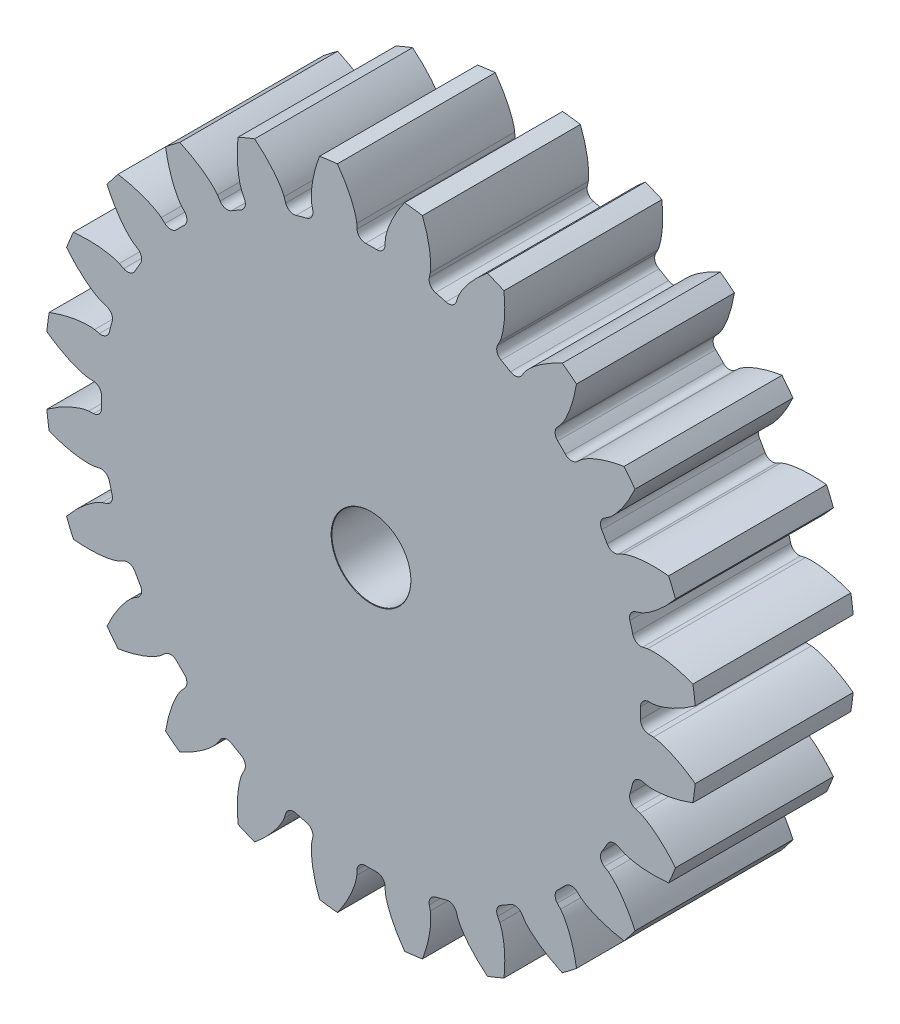
SolidWorks part; units mm, degrees
ref_plane "Front Plane" through (0, 0, 0) normal (0, 0, 1) x (1, 0, 0)
ref_plane "Top Plane" through (0, 0, 0) normal (0, 1, 0) x (1, 0, 0)
ref_plane "Right Plane" through (0, 0, 0) normal (1, 0, 0) x (0, 0, -1)
sketch "Sketch1" plane through (0, 0, 0) normal (0, 0, 1) x (1, 0, 0)
  line L0 (0, 0) -> (0, 19.05) construction
  line L1 (-6.1226, 21.2784) -> (6.1226, 16.8216) construction
  circle A0 centre (0, 0) radius 17.0656 construction
  circle A1 centre (0, 0) radius 20.6375 construction
  circle A2 centre (0, 0) radius 19.05 construction
  circle A3 centre (0, 0) radius 17.9011 construction
  point P8 (203.2, 0)
  point P13 (304.8, 0)
  dimension "OD | Outside Diameter" = 41.275
  dimension "Root Diameter" = 34.1313
  dimension "Gear Pitch Diameter" = 38.1
  dimension "Base Diameter" = 35.8023
  dimension "Pressure Angle" = 20
  dimension "Number of Teeth" = 609.6
  dimension "Gear Pitch | Diametral Pitch" = 406.4
sketch "Sketch2" plane through (0, 0, 0) normal (1, 0, 0) x (0, 0, -1)
  line L0 (-5, 0) -> (5, 0) construction
  point P2 (15.6375, 0)
  point P5 (25.9562, 0)
  point P6 (-15.6375, 0)
  dimension "Length" = 10
  dimension "D1" = 20.6375
  dimension "D2" = 30.9562
  dimension "D3" = 20.6375
sketch "Sketch3" plane through (0, 0, 0) normal (0, 0, 1) x (1, 0, 0)
  circle A0 centre (0, 0) radius 20.6375
  circle A1 centre (0, 0) radius 20.6375 construction
extrude "Boss-Extrude1" add sketch "Sketch3" against normal up to vertex (5 mm away) and the other way up to vertex (5 mm away) up to point (0, 0, -5) other way up to point (0, 0, 5)
sketch "Sketch4" plane through (0, 0, 0) normal (0, 0, 1) x (1, 0, 0)
  line L0 (0, 0) -> (17.0438, 0.8622) construction
  line L2 (0, 0) -> (17.0438, -0.8622) construction
  line L4 (17.0438, 0.8622) -> (17.8783, 0.9044)
  line L5 (17.8783, -0.9044) -> (17.0438, -0.8622)
  arc A0 (17.0438, 0.8622) -> (17.0438, -0.8622) centre (0, 0) cw
  arc A3 (20.5273, 2.1297) -> (20.5273, -2.1297) centre (0, 0) cw
  circle A4 centre (0, 0) radius 20.6375 construction
  spline S0 degree 4 poles (17.8783, 0.9044) (17.8826, 0.9047) (17.8948, 0.9056) (17.9178, 0.908) (17.9552, 0.9129) (18.0028, 0.9204) (18.0642, 0.9316) (18.1363, 0.9468) (18.2153, 0.9656) (18.3009, 0.9883) (18.3861, 1.013) (18.4708, 1.0393) (18.5549, 1.0673) (18.6565, 1.1031) (18.7778, 1.1487) (18.9188, 1.2059) (19.0779, 1.2755) (19.2391, 1.3513) (19.3967, 1.43) (19.555, 1.5141) (19.7073, 1.5988) (19.8644, 1.6914) (20.0088, 1.7793) (20.1693, 1.883) (20.2983, 1.9682) (20.4671, 2.0861) (20.5663, 2.1574) (20.6818, 2.2427) (20.7328, 2.2815) (20.7642, 2.3054) knots 0 0 0 0 0 0.005377 0.015084 0.028532 0.04661 0.064855 0.092111 0.119476 0.146842 0.174209 0.201575 0.228941 0.256307 0.307035 0.361767 0.4165 0.471232 0.525964 0.580697 0.635429 0.690161 0.744894 0.799626 0.854358 0.909091 0.954545 1 1 1 1 1 construction
  spline S1 degree 4 poles (17.8783, 0.9044) (17.8826, 0.9047) (17.8948, 0.9056) (17.9178, 0.908) (17.9552, 0.9129) (18.0028, 0.9204) (18.0642, 0.9316) (18.1363, 0.9468) (18.2153, 0.9656) (18.3009, 0.9883) (18.3861, 1.013) (18.4708, 1.0393) (18.5549, 1.0673) (18.6565, 1.1031) (18.7778, 1.1487) (18.9188, 1.2059) (19.0779, 1.2755) (19.2391, 1.3513) (19.3967, 1.43) (19.555, 1.5141) (19.7073, 1.5988) (19.8644, 1.6914) (20.0088, 1.7793) (20.1693, 1.883) (20.2983, 1.9682) (20.4305, 2.0606) (20.4946, 2.1061) (20.5273, 2.1297) knots 0 0 0 0 0 0.005377 0.015084 0.028532 0.04661 0.064855 0.092111 0.119476 0.146842 0.174209 0.201575 0.228941 0.256307 0.307035 0.361767 0.4165 0.471232 0.525964 0.580697 0.635429 0.690161 0.744894 0.799626 0.854358 0.909091 0.909091 0.909091 0.909091 0.909091
  spline S2 degree 4 poles (17.8783, -0.9044) (17.8826, -0.9047) (17.8948, -0.9056) (17.9178, -0.908) (17.9552, -0.9129) (18.0028, -0.9204) (18.0642, -0.9316) (18.1363, -0.9468) (18.2153, -0.9656) (18.3009, -0.9883) (18.3861, -1.013) (18.4708, -1.0393) (18.5549, -1.0673) (18.6565, -1.1031) (18.7778, -1.1487) (18.9188, -1.2059) (19.0779, -1.2755) (19.2391, -1.3513) (19.3967, -1.43) (19.555, -1.5141) (19.7073, -1.5988) (19.8644, -1.6914) (20.0088, -1.7793) (20.1693, -1.883) (20.2983, -1.9682) (20.4671, -2.0861) (20.5663, -2.1574) (20.6818, -2.2427) (20.7328, -2.2815) (20.7642, -2.3054) knots 0 0 0 0 0 0.005377 0.015084 0.028532 0.04661 0.064855 0.092111 0.119476 0.146842 0.174209 0.201575 0.228941 0.256307 0.307035 0.361767 0.4165 0.471232 0.525964 0.580697 0.635429 0.690161 0.744894 0.799626 0.854358 0.909091 0.954545 1 1 1 1 1 construction
  spline S3 degree 4 poles (17.8783, -0.9044) (17.8826, -0.9047) (17.8948, -0.9056) (17.9178, -0.908) (17.9552, -0.9129) (18.0028, -0.9204) (18.0642, -0.9316) (18.1363, -0.9468) (18.2153, -0.9656) (18.3009, -0.9883) (18.3861, -1.013) (18.4708, -1.0393) (18.5549, -1.0673) (18.6565, -1.1031) (18.7778, -1.1487) (18.9188, -1.2059) (19.0779, -1.2755) (19.2391, -1.3513) (19.3967, -1.43) (19.555, -1.5141) (19.7073, -1.5988) (19.8644, -1.6914) (20.0088, -1.7793) (20.1693, -1.883) (20.2983, -1.9682) (20.4305, -2.0606) (20.4946, -2.1061) (20.5273, -2.1297) knots 0 0 0 0 0 0.005377 0.015084 0.028532 0.04661 0.064855 0.092111 0.119476 0.146842 0.174209 0.201575 0.228941 0.256307 0.307035 0.361767 0.4165 0.471232 0.525964 0.580697 0.635429 0.690161 0.744894 0.799626 0.854358 0.909091 0.909091 0.909091 0.909091 0.909091
  dimension "D1" = 34.1313
extrude "Cut-Extrude1" cut sketch "Sketch4" against normal through all both and the other way through all
fillet "Fillet1" radius 0.5326 2 edges at (17.0438, -0.8622, 0) (17.0438, 0.8622, 0)
pattern_circular "CirPattern1" count 24 over 360 about axis through (0, 0, 5) along (0, 0, -1) of "Cut-Extrude1", "Fillet1"
sketch "Sketch5" plane through (0, 0, 5) normal (0, 0, 1) x (1, 0, 0)
  point P0 (0, 0)
hole_wizard "Ø5.0mm Dowel Hole1" positions "Sketch5" profile "Sketch6" hole size "Ø5.0" standard "ANSI Metric" end condition through all
sketch "Sketch6" plane through (0, 0, 5) normal (1, 0, 0) x (0, -1, 0)
  line L0 (0, 0) -> (0, 10)
  line L1 (0, 10) -> (2.5, 10)
  line L2 (2.5, 10) -> (2.5, 0.025)
  line L3 (2.5, 0.025) -> (2.525, 0)
  line L5 (2.525, 0) -> (0, 0)
  line L6 (-2.5, 0.025) -> (-2.525, 0) construction
  line L11 (0, -6.35) -> (0, 107.95) construction
  dimension "Thru Hole Dia." = 5
  dimension "Thru Hole Depth" = 10
  dimension "Near C'Sink Dia." = 5.05
  dimension "Near C'Sink Angle" = 90
equation "\"Root Diameter@Sketch1\"=\"Root Diameter\""
equation "\"OD | Outside Diameter@Sketch1\"=\"Outside Diameter\""
equation "\"D1@CirPattern1\"=\"Number of Teeth\""
equation "\"Diametral Pitch\"= 16"
equation "\"Number of Teeth\"= 24"
equation "\"Pressure Angle\"=20"
equation "\"Pitch Diameter\"= \"Number of Teeth\" / \"Diametral Pitch\""
equation "\"Base Diameter\"= \"Pitch Diameter\" * cos ( \"Pressure Angle\" )"
equation "\"Outside Diameter\"= ( \"Number of Teeth\" + 2 ) / \"Diametral Pitch\""
equation "\"Dedendum\"= 1.25 / \"Diametral Pitch\""
equation "\"Root Diameter\"= \"Pitch Diameter\" - ( 2 * \"Dedendum\" )"
equation "\"Pitch Angle\"= 360deg / \"Number of Teeth\""
equation "\"Alpha\"= sqr ( \"Pitch Diameter\" ^ 2 - \"Base Diameter\" ^ 2 ) / \"Base Diameter\" * 180 / PI - \"Pressure Angle\""
equation "\"Beta\"= ( \"Pitch Angle\" / 4 - \"Alpha\" )"
equation "\"Phi\"= sqr ( ( \"Outside Diameter\" / 2 ) ^ 2 - ( \"Base Diameter\" / 2 ) ^ 2 ) / ( \"Base Diameter\" / 2 )"
equation "\"Addendum\"= 1 / \"Diametral Pitch\""
equation "\"WorkingDepth\"= 2 / \"Diametral Pitch\""
equation "\"WholeDepth\"= 2.25 / \"Diametral Pitch\""
equation "\"Clearance\"= 0.25 / \"Diametral Pitch\""
equation "\"ToothThickness\"= ( pi * 2 ) / \"Diametral Pitch\""
equation "\"CircularPitch\"= pi / \"Diametral Pitch\""
equation "\"Number of Teeth@Sketch1\"=\"Number of Teeth\""
equation "\"Gear Pitch | Diametral Pitch@Sketch1\"=\"Diametral Pitch\""
equation "\"Pressure Angle@Sketch1\"=\"Pressure Angle\""
equation "\"Gear Pitch Diameter@Sketch1\"=\"Pitch Diameter\""
equation "\"Base Diameter@Sketch1\"=\"Base Diameter\""
equation "\"Fillet\"= \"Clearance\" * cos ( \"Pressure Angle\" ) * tan ( ( 90 + \"Pressure Angle\" ) / 2 )"
equation "\"D1@Fillet1\"=\"Fillet\""
equation "\"D1@Sketch4\"=if( \"Base Diameter\">\"Root Diameter\",\"Root Diameter\",\"Base Diameter\"-.00001)"
equation "\"D1@Sketch2\"=\"OD | Outside Diameter@Sketch1\"*2*0.5*0.5"
equation "\"D2@Sketch2\"=\"D1@Sketch2\"*1.5"
equation "\"D3@Sketch2\"=\"D1@Sketch2\""
equation "\"Length\"= 1cm"
equation "\"Length@Sketch2\"= \"Length\""
